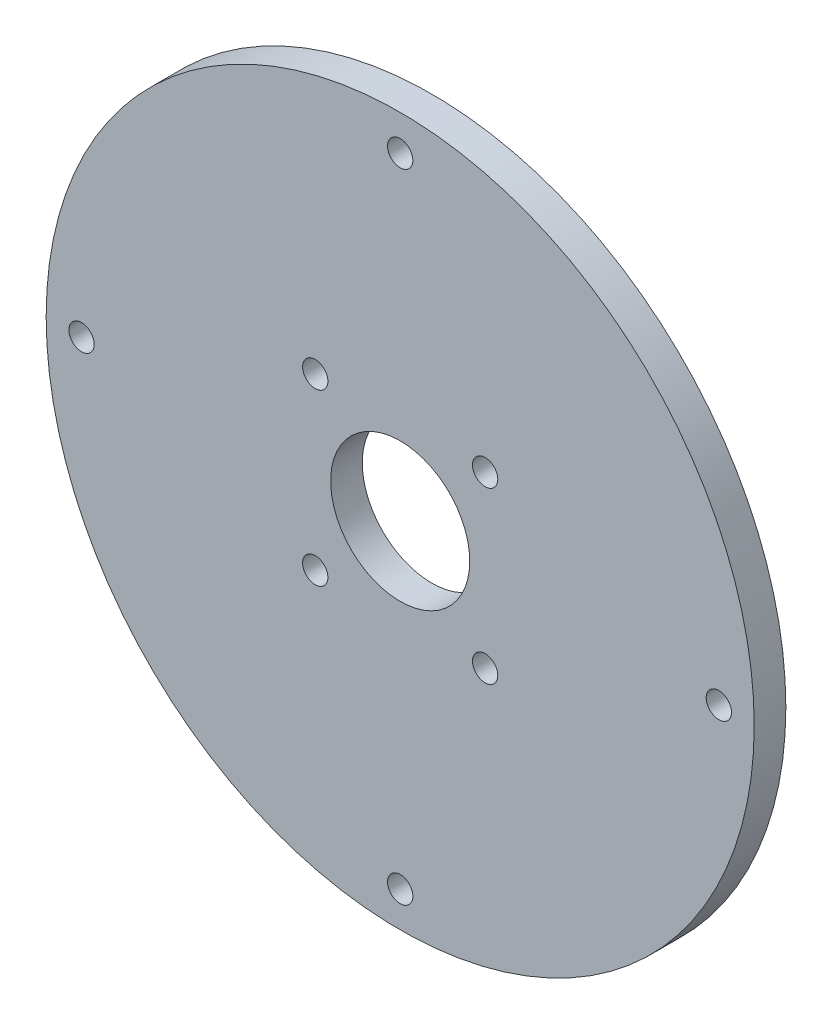
SolidWorks part; units mm, degrees
material "Thornel Mat VMA"
ref_plane "Alzado" through (0, 0, 0) normal (0, 0, 1) x (1, 0, 0)
ref_plane "Planta" through (0, 0, 0) normal (0, 1, 0) x (1, 0, 0)
ref_plane "Vista lateral" through (0, 0, 0) normal (1, 0, 0) x (0, 0, -1)
sketch "Croquis1" plane through (0, 0, 0) normal (0, 0, 1) x (1, 0, 0)
  line L0 (17.5, 0) -> (32.5, 0) construction
  line L1 (-32.5, -32.5) -> (32.5, -32.5)
  line L2 (-32.5, -32.5) -> (-32.5, 32.5)
  line L3 (-32.5, 32.5) -> (32.5, 32.5)
  line L4 (32.5, -32.5) -> (32.5, 32.5)
  line L5 (-32.5, -32.5) -> (32.5, 32.5) construction
  line L6 (-32.5, 32.5) -> (32.5, -32.5) construction
  line L7 (0, 17.5) -> (0, 32.5) construction
  circle A0 centre (0, 0) radius 17.5 construction
  circle A5 centre (-27.5503, 27.5503) radius 3 construction
  circle A6 centre (27.5503, 27.5503) radius 3 construction
  circle A7 centre (27.5503, -27.5503) radius 3 construction
  circle A8 centre (-27.5503, -27.5503) radius 3 construction
  circle A9 centre (0, 0) radius 5.5
  circle A10 centre (0, 0) radius 9.5 construction
  circle A11 centre (-6.7175, 6.7175) radius 1
  circle A12 centre (6.7175, 6.7175) radius 1
  circle A13 centre (6.7175, -6.7175) radius 1
  circle A14 centre (-6.7175, -6.7175) radius 1
  point P0 (0, 0)
  point P21 (0, 0)
  point P32 (0, 0)
  point P35 (0, 0)
  dimension "D1" = 35
  dimension "D2" = 19
  dimension "D6" = 6
  dimension "D9" = 65
  dimension "D3" = 2
  dimension "D10" = 11
  dimension "D5" = 15
  dimension "D8" = 7
  dimension "D7" = 4
  dimension "D4" = 4
extrude "Saliente-Extruir1" add sketch "Croquis1" along normal blind 2.5
fillet "Redondeo1" radius 15 4 edges at (32.5, 32.5, 1.25) (32.5, -32.5, 1.25) (-32.5, -32.5, 1.25) (-32.5, 32.5, 1.25)
sketch "Croquis2" plane through (0, 0, 2.5) normal (0, 0, 1) x (1, 0, 0)
  circle A9 centre (-26, 0) radius 3.5
  circle A12 centre (0, 26) radius 3.5
  circle A13 centre (26, 0) radius 3.5
  circle A14 centre (0, -26) radius 3.5
  circle A15 centre (0, 0) radius 20 construction
  point P27 (0, 0)
  point P36 (0, 0)
  dimension "D3" = 7
  dimension "D6" = 40
  dimension "D4" = 26
  dimension "D5" = 4
sketch "Croquis3" plane through (0, 0, 2.5) normal (0, 0, 1) x (1, 0, 0)
  line L0 (0, 0) -> (-27.5503, 27.5503) construction
  line L1 (0, 0) -> (-26, 0) construction
  line L2 (-13.435, 13.435) -> (-2.1213, 24.7487) construction
  line L4 (-2.1213, 24.7487) -> (-5.6569, 28.2843) construction
  line L5 (-5.6569, 28.2843) -> (-28.2843, 5.6569) construction
  line L6 (-28.2843, 5.6569) -> (-24.7487, 2.1213) construction
  line L7 (-24.7487, 2.1213) -> (-13.435, 13.435) construction
  line L8 (-13.435, 13.435) -> (-13.0108, 13.0108) construction
  circle A0 centre (0, 0) radius 18.4 construction
  circle A1 centre (-24.7487, 5.6569) radius 1
  circle A2 centre (-5.6569, 24.7487) radius 1
  circle A3 centre (5.6569, 24.7487) radius 1
  circle A4 centre (24.7487, 5.6569) radius 1
  circle A5 centre (24.7487, -5.6569) radius 1
  circle A6 centre (5.6569, -24.7487) radius 1
  circle A7 centre (-5.6569, -24.7487) radius 1
  circle A8 centre (-24.7487, -5.6569) radius 1
  point P31 (0, 0)
  dimension "D1" = 36.8
  dimension "D5" = 2.5
  dimension "D7" = 19
  dimension "D8" = 2
  dimension "D2" = 5
  dimension "D3" = 16
  dimension "D4" = 32
  dimension "D6" = 2.5
  dimension "D9" = 4
extrude "Cortar-Extruir2" [suppressed] cut sketch "Croquis3" against normal up to vertex
sketch "Croquis5" plane through (0, 0, 2.5) normal (0, 0, 1) x (1, 0, 0)
  circle A0 centre (0, 0) radius 28
  circle A1 centre (0, 0) radius 47.6659
  dimension "D1" = 56
extrude "Cortar-Extruir3" cut sketch "Croquis5" against normal up to vertex (2.5 mm away)
sketch "Croquis6" [suppressed] plane through (0, 0, 2) normal (0, 0, 1) x (1, 0, 0)
  line L0 (5.6569, -24.7487) -> (24.7487, -5.6569) construction
  line L1 (24.7487, -5.6569) -> (26.5165, -3.8891) construction
  line L2 (24.7487, -5.6569) -> (22.981, -3.8891) construction
  line L3 (5.6569, -24.7487) -> (3.8891, -26.5165) construction
  line L4 (24.7487, -2.1213) -> (2.1213, -24.7487)
  line L5 (24.7487, -2.1213) -> (27.5618, -4.9344)
  line L6 (2.1213, -24.7487) -> (4.9344, -27.5618)
  line L7 (6.7725, -27.1686) -> (27.1686, -6.7725)
  line L8 (15.2028, -15.2028) -> (16.9706, -16.9706) construction
  circle A0 centre (0, 0) radius 28 construction
  arc A1 (27.5618, -4.9344) -> (27.1686, -6.7725) centre (0, 0) cw
  arc A2 (4.9344, -27.5618) -> (6.7725, -27.1686) centre (0, 0) ccw
  circle A3 centre (5.6569, -24.7487) radius 1.6
  circle A4 centre (24.7487, -5.6569) radius 1.6
  circle A5 centre (0, 0) radius 18.4 construction
  dimension "D4" = 36.8
  dimension "D1" = 2.5
  dimension "D2" = 2.5
  dimension "D3" = 2.5
  dimension "D5" = 2.5
  dimension "D6" = 2.5
  dimension "D7" = 2.5
sketch "Croquis7" plane through (0, 0, 2.5) normal (0, 0, 1) x (1, 0, 0)
  line L0 (0, 0) -> (0, 25.2) construction
  line L1 (0, 27) -> (0, 28) construction
  circle A0 centre (0, 25.2) radius 1
  circle A1 centre (0, 0) radius 28 construction
  circle A2 centre (25.2, 0) radius 1
  circle A3 centre (0, -25.2) radius 1
  circle A4 centre (-25.2, 0) radius 1
  circle A5 centre (0, 25.2) radius 1.8 construction
  point P16 (0, 0)
  dimension "D1" = 2
  dimension "D2" = 3.6
  dimension "D4" = 1
  dimension "D3" = 4
extrude "Cortar-Extruir4" cut sketch "Croquis7" against normal up to surface (2.5 mm away) up to face at (-5.7175, -6.7175, 0)
sketch "Croquis8" plane through (0, 0, 2.5) normal (0, 0, 1) x (1, 0, 0)
  line L0 (0, 23.6) -> (0, 22.6)
  circle A0 centre (0, 25.2) radius 1.6
  circle A1 centre (0, 0) radius 22.6
  circle A2 centre (0, 0) radius 28
  dimension "D1" = 3.2
  dimension "D3" = 45.2
  dimension "D4" = 56
  dimension "D2" = 1
